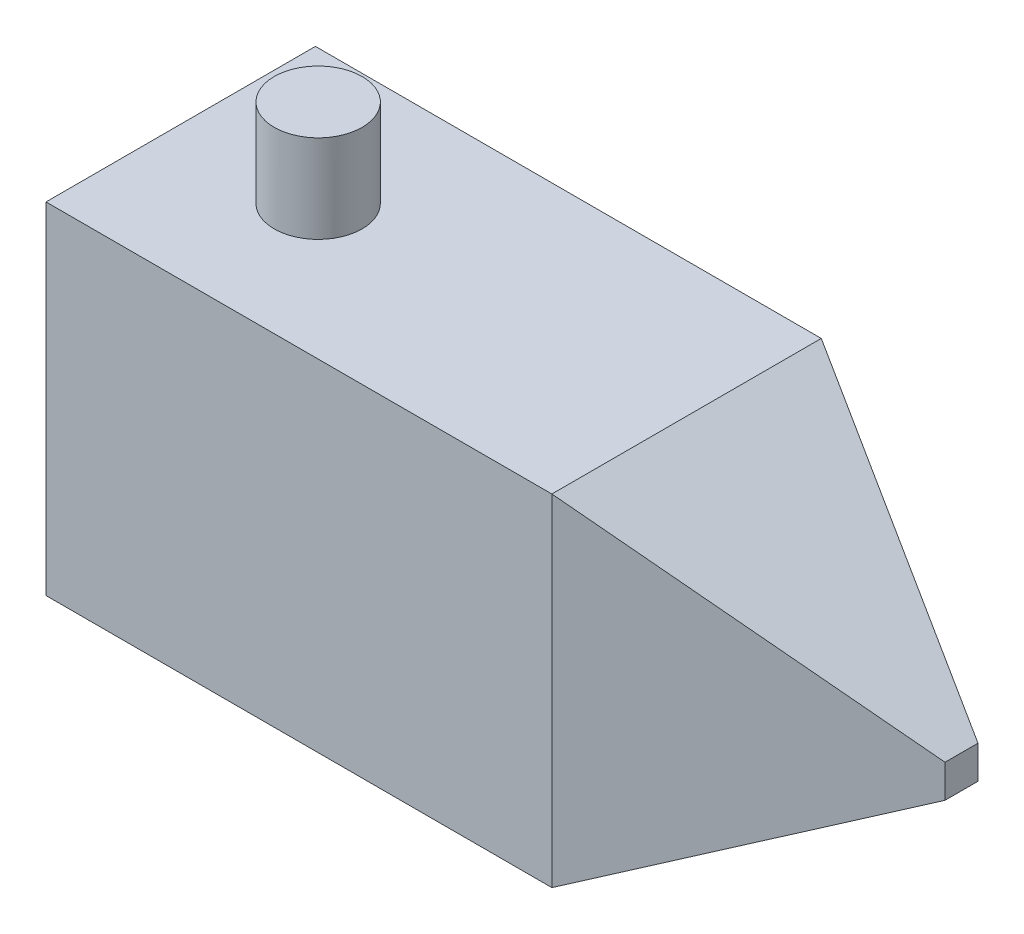
SolidWorks part; units mm, degrees
ref_plane "Front Plane" through (0, 0, 0) normal (0, 0, 1) x (1, 0, 0)
ref_plane "Top Plane" through (0, 0, 0) normal (0, 1, 0) x (1, 0, 0)
ref_plane "Right Plane" through (0, 0, 0) normal (1, 0, 0) x (0, 0, -1)
sketch "Sketch1" plane through (0, 0, 0) normal (0, 1, 0) x (1, 0, 0)
  line L1 (-23, -12.25) -> (23, -12.25)
  line L2 (-23, -12.25) -> (-23, 12.25)
  line L3 (-23, 12.25) -> (23, 12.25)
  line L4 (23, -12.25) -> (23, 12.25)
  line L5 (-23, -12.25) -> (23, 12.25) construction
  line L6 (-23, 12.25) -> (23, -12.25) construction
  point P0 (0, 0)
  dimension "D1" = 24.5
  dimension "D2" = 46
extrude "Body" add sketch "Sketch1" along normal blind 31
sketch "Sketch3" plane through (0, 0, 0) normal (0, 1, 0) x (1, 0, 0)
  line L0 (-23, -12.25) -> (23, -12.25) construction
  line L1 (-21, 10.25) -> (21, 10.25)
  line L2 (-21, 10.25) -> (-21, -10.25)
  line L3 (-21, -10.25) -> (21, -10.25)
  line L4 (21, 10.25) -> (21, -10.25)
  line L5 (-21, 10.25) -> (21, -10.25) construction
  line L6 (-21, -10.25) -> (21, 10.25) construction
  line L7 (23, -12.25) -> (23, 12.25) construction
  point P0 (0, 0)
  dimension "D1" = 2
  dimension "D2" = 2
extrude "Servo Hole" cut sketch "Sketch3" along normal blind 29
ref_plane "Point plane" through (48, 0, 0) normal (1, 0, 0) x (0, 0, -1)
sketch "Point" plane through (48, 0, 0) normal (1, 0, 0) x (0, 0, -1)
  line L1 (-1.5, 14) -> (1.5, 14)
  line L2 (-1.5, 14) -> (-1.5, 17)
  line L3 (-1.5, 17) -> (1.5, 17)
  line L4 (1.5, 14) -> (1.5, 17)
  line L5 (-1.5, 14) -> (1.5, 17) construction
  line L6 (-1.5, 17) -> (1.5, 14) construction
  line L8 (12.25, 31) -> (-12.25, 0) construction
  point P0 (0, 15.5)
  dimension "D1" = 3
  dimension "D2" = 3
loft "Loft1" add profiles "Point" section "Point" section face at (23, 15.5, 0)
sketch "Sketch5" plane through (-23, 0, 0) normal (-1, 0, 0) x (0, 0, 1)
  line L8 (-6, 27) -> (6, 27)
  line L13 (6, 27) -> (6, 22)
  line L14 (6, 22) -> (4.5, 22)
  line L17 (4.5, 22) -> (4.5, 2)
  line L18 (4.5, 2) -> (-4.5, 2)
  line L19 (-12.25, 0) -> (12.25, 0) construction
  line L21 (-4.5, 2) -> (-4.5, 22)
  line L22 (-4.5, 22) -> (-6, 22)
  line L23 (-6, 22) -> (-6, 27)
  line L25 (-12.25, 31) -> (12.25, 31) construction
  dimension "D1" = 4
  dimension "D2" = 2
  dimension "D3" = 5
  dimension "D4" = 12
  dimension "D5" = 5
  dimension "D6" = 1.5
  dimension "D7" = 1.5
  dimension "D8" = 4.5
extrude "Cut-Extrude3" cut sketch "Sketch5" against normal blind 29
sketch "Sketch6" plane through (0, 31, 0) normal (0, 1, 0) x (1, 0, 0)
  line L2 (-10.5, 0) -> (0, 0) construction
  line L3 (-23, 12.25) -> (-23, -12.25) construction
  circle A0 centre (-10.5, 0) radius 4
  point P3 (-23, 0)
  dimension "D2" = 8
  dimension "D1" = 12.5
extrude "Boss-Extrude3" add sketch "Sketch6" along normal blind 8
